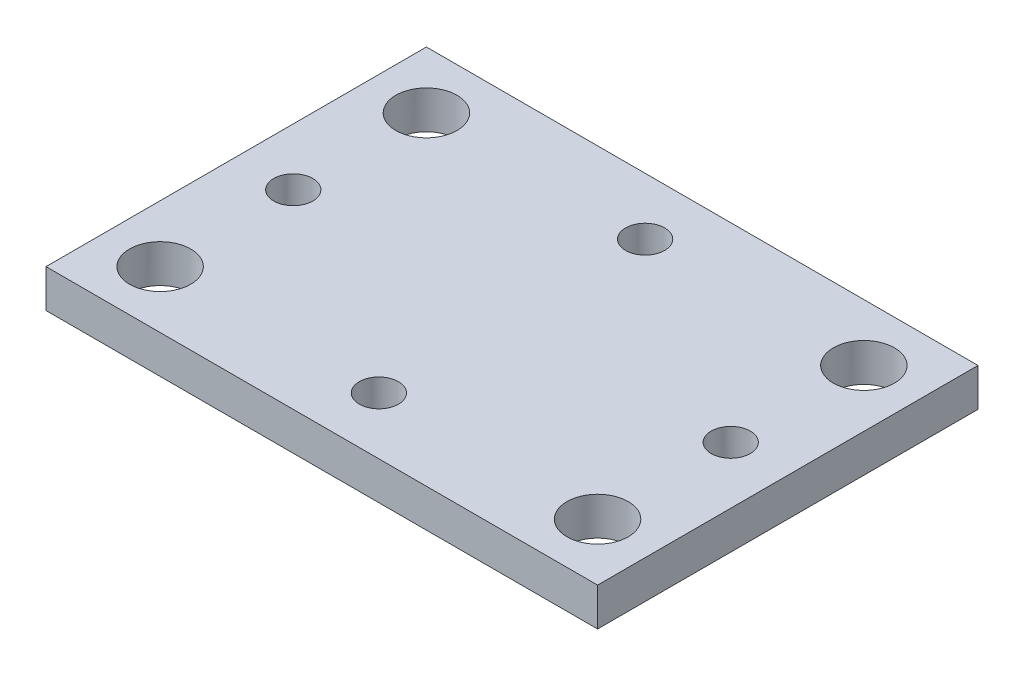
SolidWorks part; units mm, degrees
material "ABS"
ref_plane "Front Plane" through (0, 0, 0) normal (0, 0, 1) x (1, 0, 0)
ref_plane "Top Plane" through (0, 0, 0) normal (0, 1, 0) x (1, 0, 0)
ref_plane "Right Plane" through (0, 0, 0) normal (1, 0, 0) x (0, 0, -1)
sketch "Sketch1" plane through (0, 0, 0) normal (0, 1, 0) x (1, 0, 0)
  line L0 (-23.0188, 15.875) -> (23.0187, 15.875)
  line L1 (-18.2563, -11.1125) -> (18.2562, -11.1125) construction
  line L2 (-18.2563, -11.1125) -> (-18.2563, 11.1125) construction
  line L3 (-18.2563, 11.1125) -> (18.2562, 11.1125) construction
  line L4 (18.2562, -11.1125) -> (18.2562, 11.1125) construction
  line L5 (-18.2563, -11.1125) -> (18.2562, 11.1125) construction
  line L6 (-18.2563, 11.1125) -> (18.2562, -11.1125) construction
  line L7 (23.0187, -15.875) -> (23.0187, 15.875)
  line L8 (-23.0188, -15.875) -> (23.0187, -15.875)
  line L9 (-23.0188, -15.875) -> (-23.0188, 15.875)
  point P0 (0, 0)
  point P6 (0, 0)
  dimension "D1" = 36.5125
  dimension "D2" = 22.225
  dimension "D3" = 4.7625
extrude "Boss-Extrude1" add sketch "Sketch1" along normal blind 3.175
hole_wizard "#10 Clearance Hole1" positions "Sketch3" profile "Sketch2" hole size "#10" standard "ANSI Inch" end condition up to next
sketch "Sketch3" plane through (0, 3.175, 0) normal (0, 1, 0) x (1, 0, 0)
  line L13 (-18.2563, 11.1125) -> (-18.2563, -11.1125)
  line L14 (-18.2563, -11.1125) -> (18.2562, -11.1125)
  line L15 (18.2562, -11.1125) -> (18.2562, 11.1125)
  line L16 (18.2562, 11.1125) -> (-18.2563, 11.1125)
  line L17 (-18.2563, 11.1125) -> (-18.2563, -11.1125) construction
  line L18 (-18.2563, -11.1125) -> (18.2562, -11.1125) construction
  line L19 (18.2562, -11.1125) -> (18.2562, 11.1125) construction
  line L20 (18.2562, 11.1125) -> (-18.2563, 11.1125) construction
  point P179 (-18.2563, 11.1125)
  point P180 (-18.2563, -11.1125)
  point P181 (18.2562, -11.1125)
  point P182 (18.2562, 11.1125)
  dimension "D1" = 4.7625
sketch "Sketch2" plane through (-18.2563, 3.175, -11.1125) normal (1, 0, 0) x (0, 0, 1)
  line L0 (0, 0) -> (0, 3.175)
  line L1 (0, 3.175) -> (2.5527, 3.175)
  line L2 (2.5527, 3.175) -> (2.5527, 0)
  line L5 (2.5527, 0) -> (0, 0)
  line L11 (0, -6.35) -> (0, 107.95) construction
  dimension "Thru Hole Dia." = 5.1054
  dimension "Thru Hole Depth" = 3.175
hole_wizard "#4 Clearance Hole1" positions "Sketch5" profile "Sketch4" hole size "#4" standard "ANSI Inch" end condition up to next
sketch "Sketch5" plane through (0, 3.175, 0) normal (0, 1, 0) x (1, 0, 0)
  line L8 (18.2563, -11.1125) -> (-18.2563, -11.1125) construction
  line L9 (18.2563, -11.1125) -> (18.2563, 11.1125) construction
  line L10 (18.2563, 11.1125) -> (-18.2563, 11.1125) construction
  line L11 (-18.2563, -11.1125) -> (-18.2563, 11.1125) construction
  line L12 (18.2563, -11.1125) -> (-18.2563, 11.1125) construction
  line L13 (18.2563, 11.1125) -> (-18.2563, -11.1125) construction
  point P110 (0, 11.1125)
  point P112 (0, -11.1125)
  point P114 (-18.2563, 0)
  point P116 (18.2563, 0)
  dimension "D1" = 36.5125
  dimension "D2" = 22.225
sketch "Sketch4" plane through (0, 3.175, -11.1125) normal (1, 0, 0) x (0, 0, 1)
  line L0 (0, 0) -> (0, 3.175)
  line L1 (0, 3.175) -> (1.6319, 3.175)
  line L2 (1.6319, 3.175) -> (1.6319, 0)
  line L5 (1.6319, 0) -> (0, 0)
  line L11 (0, -6.35) -> (0, 107.95) construction
  dimension "Thru Hole Dia." = 3.2639
  dimension "Thru Hole Depth" = 3.175
